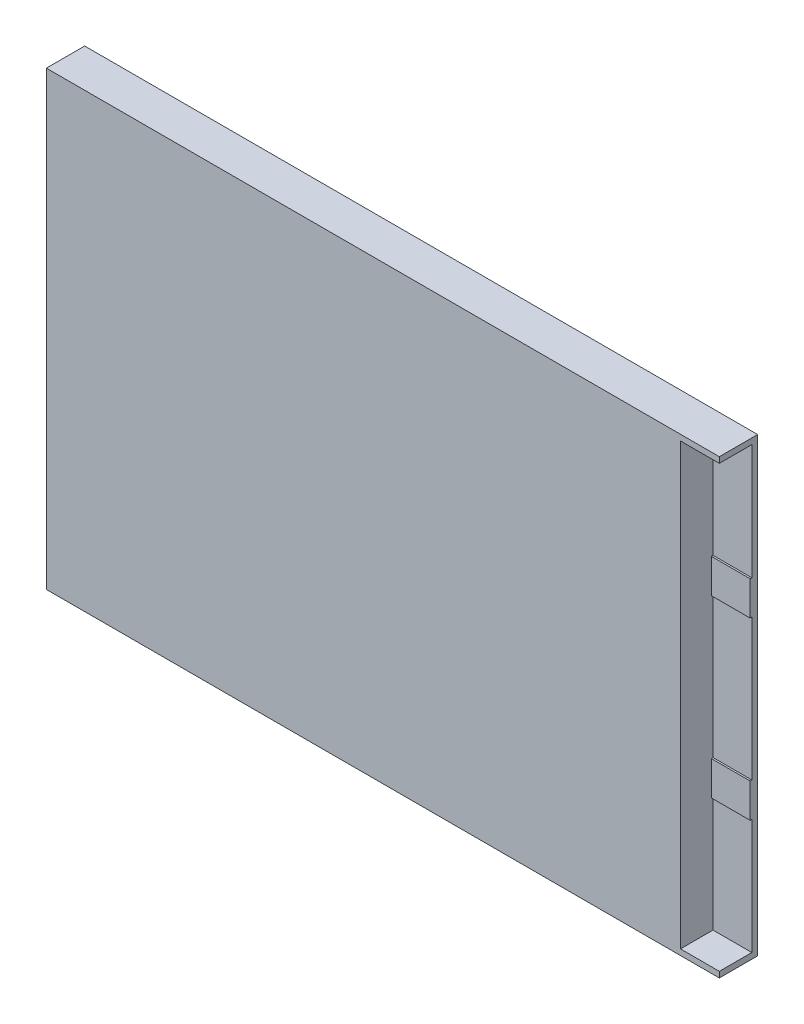
SolidWorks part; units mm, degrees
ref_plane "Front Plane" through (0, 0, 0) normal (0, 0, 1) x (1, 0, 0)
ref_plane "Top Plane" through (0, 0, 0) normal (0, 1, 0) x (1, 0, 0)
ref_plane "Right Plane" through (0, 0, 0) normal (1, 0, 0) x (0, 0, -1)
sketch "Sketch1" plane through (0, 0, 0) normal (0, 0, 1) x (1, 0, 0)
  line L1 (-50.165, -33.655) -> (50.165, -33.655)
  line L2 (-50.165, -33.655) -> (-50.165, 33.655)
  line L3 (-50.165, 33.655) -> (50.165, 33.655)
  line L4 (50.165, -33.655) -> (50.165, 33.655)
  line L5 (-50.165, -33.655) -> (50.165, 33.655) construction
  line L6 (-50.165, 33.655) -> (50.165, -33.655) construction
  point P0 (0, 0)
  dimension "D1" = 67.31
  dimension "D2" = 100.33
extrude "Boss-Extrude1" add sketch "Sketch1" along normal mid plane 5.715
sketch "Sketch2" plane through (0, 0, 2.8575) normal (0, 0, 1) x (1, 0, 0)
  line L0 (50.165, -33.655) -> (50.165, 33.655) construction
  line L1 (50.165, -32.7914) -> (44.3738, -32.7914)
  line L2 (50.165, -32.7914) -> (50.165, 32.7914)
  line L3 (50.165, 32.7914) -> (44.3738, 32.7914)
  line L4 (44.3738, -32.7914) -> (44.3738, 32.7914)
  line L5 (44.3738, 32.7914) -> (44.3738, 33.655) construction
  line L6 (50.165, 33.655) -> (-50.165, 33.655) construction
  line L7 (44.3738, -32.7914) -> (44.3738, -33.655) construction
  line L8 (-50.165, -33.655) -> (50.165, -33.655) construction
  dimension "D1" = 0.8636
  dimension "D2" = 5.7912
extrude "Cut-Extrude1" cut sketch "Sketch2" against normal offset from surface (4.8514 mm away) 0.8636 up to face at (0, 0, -2.8575)
sketch "Sketch3" plane through (0, 0, -1.9939) normal (0, 0, 1) x (1, 0, 0)
  line L0 (50.165, -32.7914) -> (50.165, 32.7914) construction
  line L1 (50.165, -15.5956) -> (44.3738, -15.5956)
  line L2 (50.165, -15.5956) -> (50.165, -10.5156)
  line L3 (50.165, -10.5156) -> (44.3738, -10.5156)
  line L4 (44.3738, -15.5956) -> (44.3738, -10.5156)
  line L5 (44.3738, 32.7914) -> (44.3738, -32.7914) construction
  line L6 (44.3738, -32.7914) -> (50.165, -32.7914) construction
  line L7 (50.165, 10.5156) -> (44.3738, 10.5156)
  line L8 (50.165, 10.5156) -> (50.165, 15.5956)
  line L9 (50.165, 15.5956) -> (44.3738, 15.5956)
  line L10 (44.3738, 10.5156) -> (44.3738, 15.5956)
  line L11 (50.165, -15.5956) -> (50.165, -32.7914) construction
  line L12 (50.165, 15.5956) -> (50.165, 32.7914) construction
  dimension "D1" = 5.08
  dimension "D2" = 17.1958
extrude "Boss-Extrude2" add sketch "Sketch3" along normal blind 0.254
